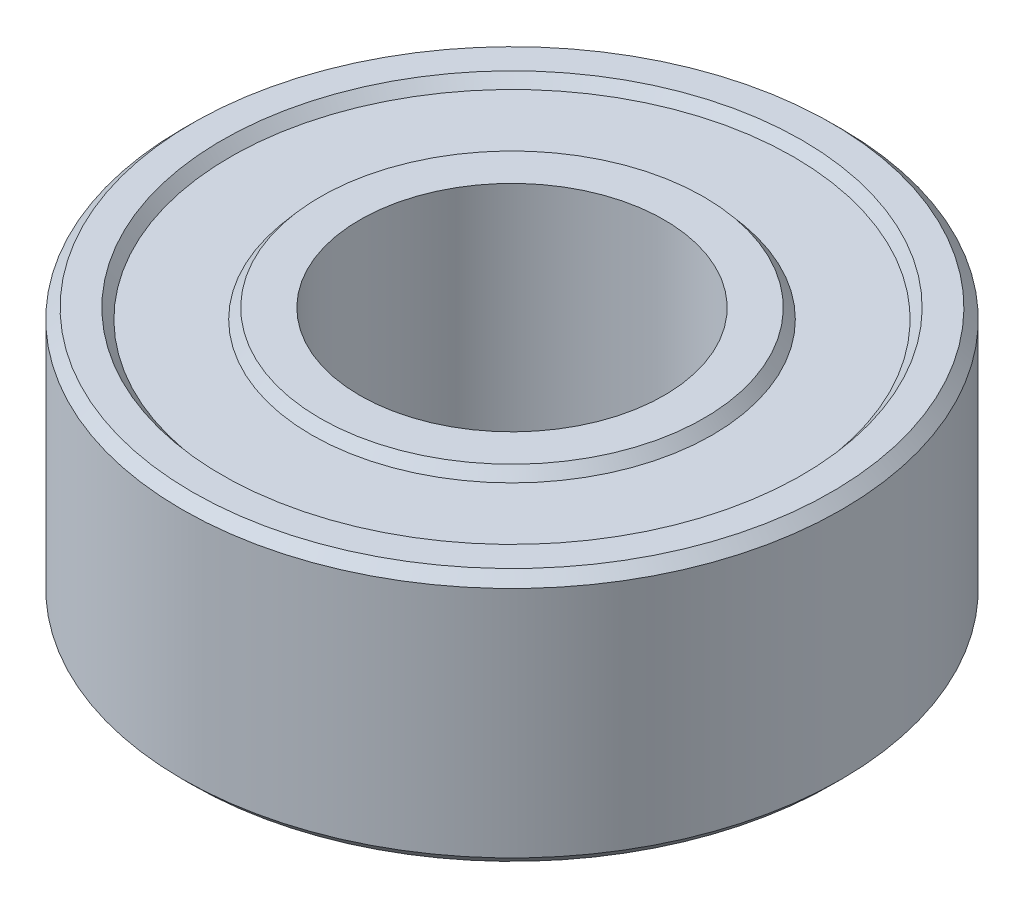
SolidWorks part; units mm, degrees
ref_plane "前视基准面" through (0, 0, 0) normal (0, 0, 1) x (1, 0, 0)
ref_plane "上视基准面" through (0, 0, 0) normal (0, 1, 0) x (1, 0, 0)
ref_plane "右视基准面" through (0, 0, 0) normal (1, 0, 0) x (0, 0, -1)
other "Configuration Table"
sketch "草图1" plane through (0, 0, 0) normal (0, 1, 0) x (1, 0, 0)
  circle A0 centre (0, 0) radius 6.5
  circle A1 centre (0, 0) radius 3
  dimension "D1" = 13
  dimension "D2" = 6
extrude "凸台-拉伸1" add sketch "草图1" along normal blind 5
sketch "草图2" plane through (0, 0, 0) normal (1, 0, 0) x (0, 0, -1)
  line L0 (3, 5) -> (-3, 5) construction
  line L1 (6.5, 5) -> (-6.5, 5) construction
  line L2 (-6.5, 5) -> (-3, 5) construction
  line L3 (3, 5) -> (-3, 5) construction
  line L4 (6.5, 5) -> (-3, 5) construction
  line L5 (-4.75, 5) -> (-4.75, 0) construction
  line L6 (-6.5, 0) -> (6.5, 0) construction
  line L7 (-5.7178, 5) -> (-5.55, 4.8)
  line L8 (-5.55, 4.8) -> (-3.95, 4.8)
  line L9 (-3.95, 4.8) -> (-3.7822, 5)
  line L10 (-5.7178, 5) -> (-3.7822, 5)
  line L11 (-4.75, 2.5) -> (-2.2384, 2.5) construction
  line L12 (-3.95, 0.2) -> (-3.7822, 0)
  line L13 (-5.7178, 0) -> (-3.7822, 0)
  line L14 (-5.7178, 0) -> (-5.55, 0.2)
  line L15 (-5.55, 0.2) -> (-3.95, 0.2)
  line L16 (0, 0) -> (0, 5) construction
  point P2 (-6.5, 5)
  point P5 (-3, 5)
  dimension "D1" = 0.2
  dimension "D2" = 130
  dimension "D3" = 130
  dimension "D4" = 0.8
  dimension "D5" = 1.6
revolve "切除-旋转1" cut sketch "草图2" angle 360 about L16
chamfer "倒角1" distance 0.2 angle 45 2 edges at (0, 0, 6.5) (0, 5, 6.5)
